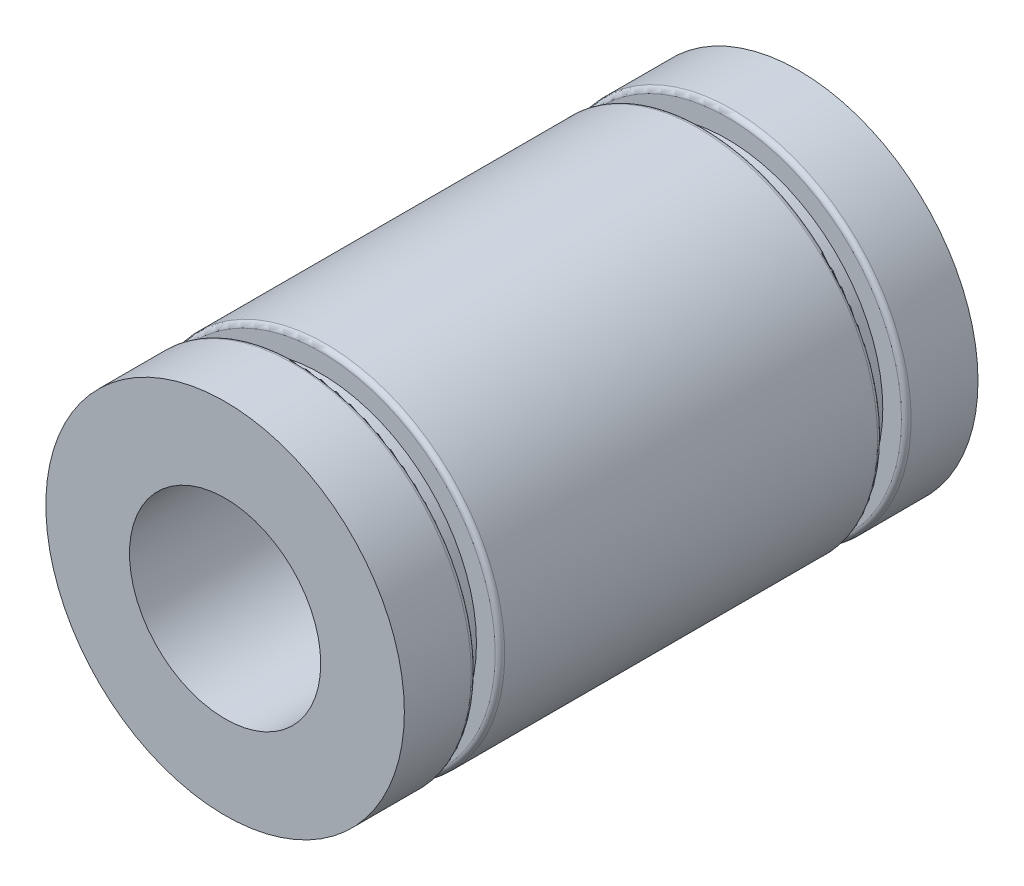
SolidWorks part; units mm, degrees
ref_plane "前视基准面" through (0, 0, 0) normal (0, 0, 1) x (1, 0, 0)
ref_plane "上视基准面" through (0, 0, 0) normal (0, 1, 0) x (1, 0, 0)
ref_plane "右视基准面" through (0, 0, 0) normal (1, 0, 0) x (0, 0, -1)
sketch "草图1" plane through (0, 0, 0) normal (0, 0, 1) x (1, 0, 0)
  circle A0 centre (0, 0) radius 4
  circle A1 centre (0, 0) radius 7.5
  dimension "D1" = 8
  dimension "D2" = 15
extrude "凸台-拉伸1" add sketch "草图1" along normal blind 24
sketch "草图4" plane through (0, 0, 0) normal (1, 0, 0) x (0, 0, -1)
  line L0 (-21, 7.5168) -> (-20, 7.5168)
  line L1 (-4, 7.5168) -> (-3, 7.5168)
  line L2 (-24, 7.5) -> (-24, -7.5) construction
  line L3 (0, -7.5) -> (0, 7.5) construction
  line L4 (-21, 7.5168) -> (-21, 6.5168)
  line L5 (-21, 6.5168) -> (-20, 6.5168)
  line L6 (-20, 6.5168) -> (-20, 7.5168)
  line L7 (-4, 7.5168) -> (-4, 6.5168)
  line L8 (-4, 6.5168) -> (-3, 6.5168)
  line L9 (-3, 6.5168) -> (-3, 7.5168)
  line L10 (0, 0) -> (-24, 0) construction
  dimension "D1" = 3
  dimension "D2" = 3
  dimension "D3" = 1
  dimension "D4" = 1
  dimension "D5" = 1
  dimension "D6" = 1
revolve "切除-旋转1" cut sketch "草图4" angle 360 about L10
fillet "圆角1" radius 0.2 4 edges at (-7.5, 0, 3) (7.5, 0, 4) (-7.5, 0, 20) (7.5, 0, 21)
